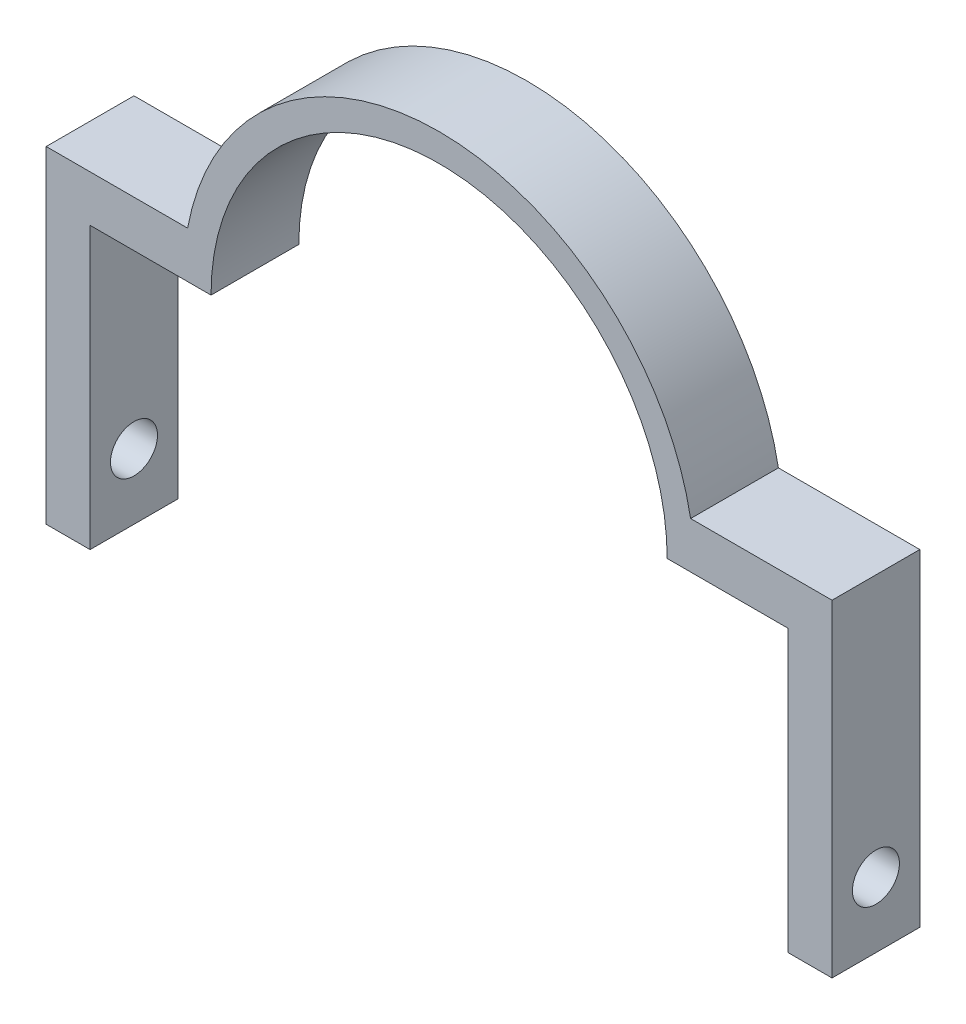
SolidWorks part; units mm, degrees
ref_plane "Front Plane" through (0, 0, 0) normal (0, 0, 1) x (1, 0, 0)
ref_plane "Top Plane" through (0, 0, 0) normal (0, 1, 0) x (1, 0, 0)
ref_plane "Right Plane" through (0, 0, 0) normal (1, 0, 0) x (0, 0, -1)
sketch "Sketch1" plane through (0, 0, 0) normal (0, 0, 1) x (1, 0, 0)
  line L3 (-16.5, 0) -> (-25.25, 0)
  line L4 (16.5, 0) -> (25.25, 0)
  line L5 (25.25, 0) -> (25.25, -20.32)
  line L6 (25.25, -20.32) -> (28.425, -20.32)
  line L7 (28.425, -20.32) -> (28.425, 3.3501)
  line L8 (28.425, 3.3501) -> (18.1941, 3.3501)
  line L9 (-28.425, 3.3501) -> (-18.1941, 3.3501)
  line L13 (-25.25, 0) -> (-25.25, -20.32)
  line L14 (-25.25, -20.32) -> (-28.425, -20.32)
  line L15 (-28.425, -20.32) -> (-28.425, 3.3501)
  arc A0 (16.5, 0) -> (-16.5, 0) centre (0, 0) ccw
  arc A1 (18.1941, 3.3501) -> (-18.1941, 3.3501) centre (0, 0) ccw
  dimension "D1" = 33
  dimension "D2" = 37
  dimension "D3" = 8.75
  dimension "D4" = 3.175
  dimension "D5" = 8.75
  dimension "D6" = 20.32
  dimension "D7" = 23.6701
  dimension "D8" = 20.32
  dimension "D9" = 23.6701
  dimension "D10" = 3.175
extrude "Boss-Extrude1" add sketch "Sketch1" along normal blind 6.35
sketch "Sketch2" plane through (28.425, 0, 0) normal (1, 0, 0) x (0, 0, -1)
  line L0 (-6.35, -20.32) -> (0, -20.32) construction
  line L2 (-6.35, 3.3501) -> (0, 3.3501) construction
  circle A0 centre (-3.175, -15.5878) radius 1.7
  point P4 (-3.175, -20.32)
  point P9 (-3.175, 3.3501)
  dimension "D1" = 3.4
  dimension "D3" = 18.938
  dimension "D2" = 0
extrude "Cut-Extrude1" cut sketch "Sketch2" against normal through all
